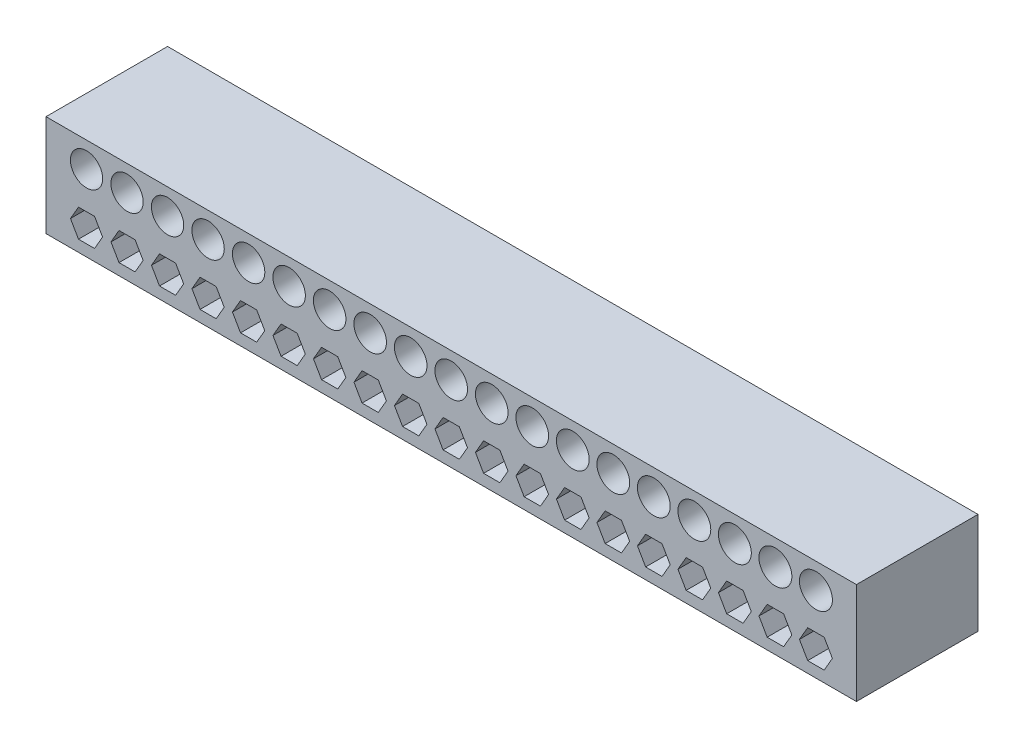
SolidWorks part; units mm, degrees
ref_plane "Front Plane" through (0, 0, 0) normal (0, 0, 1) x (1, 0, 0)
ref_plane "Top Plane" through (0, 0, 0) normal (0, 1, 0) x (1, 0, 0)
ref_plane "Right Plane" through (0, 0, 0) normal (1, 0, 0) x (0, 0, -1)
sketch "Sketch1" plane through (0, 0, 0) normal (0, 0, 1) x (1, 0, 0)
  line L0 (-93.9567, 6.25) -> (-91.9783, 9.6766) construction
  line L1 (-100, -12.5) -> (100, -12.5)
  line L2 (-100, -12.5) -> (-100, 12.5)
  line L3 (-100, 12.5) -> (100, 12.5)
  line L4 (100, -12.5) -> (100, 12.5)
  line L5 (-100, -12.5) -> (100, 12.5) construction
  line L6 (0, 12.5) -> (0, 0)
  line L7 (-91.9783, 9.6766) -> (-88.0217, 9.6766) construction
  line L8 (-88.0217, 9.6766) -> (-86.0433, 6.25) construction
  line L9 (-88.0217, 2.8234) -> (-91.9783, 2.8234) construction
  line L10 (-86.0433, 6.25) -> (-88.0217, 2.8234) construction
  line L11 (-91.9783, 2.8234) -> (-93.9567, 6.25) construction
  line L12 (-93.9567, 6.25) -> (-91.9783, 9.6766) construction
  line L13 (-91.9783, 9.6766) -> (-88.0217, 9.6766) construction
  line L14 (-88.0217, 9.6766) -> (-86.0433, 6.25) construction
  line L15 (-88.0217, 2.8234) -> (-91.9783, 2.8234) construction
  line L16 (-86.0433, 6.25) -> (-88.0217, 2.8234) construction
  line L17 (-91.9783, 2.8234) -> (-93.9567, 6.25) construction
  line L18 (0, 0) -> (0, -12.5)
  line L25 (-3.9567, -6.25) -> (-1.9783, -2.8234) construction
  line L26 (-13.9567, -6.25) -> (-11.9783, -2.8234) construction
  line L27 (-1.9783, -2.8234) -> (1.9783, -2.8234) construction
  line L28 (1.9783, -2.8234) -> (3.9567, -6.25) construction
  line L29 (1.9783, -9.6766) -> (-1.9783, -9.6766) construction
  line L30 (3.9567, -6.25) -> (1.9783, -9.6766) construction
  line L31 (-1.9783, -9.6766) -> (-3.9567, -6.25) construction
  line L32 (-1.9783, -9.6766) -> (1.9783, -2.8234) construction
  line L33 (-3.9567, -6.25) -> (3.9567, -6.25) construction
  line L34 (1.9783, -9.6766) -> (-1.9783, -2.8234) construction
  line L35 (-11.9783, -2.8234) -> (-8.0217, -2.8234) construction
  line L36 (-8.0217, -2.8234) -> (-6.0433, -6.25) construction
  line L37 (-6.0433, -6.25) -> (-8.0217, -9.6766) construction
  line L38 (-11.9783, -9.6766) -> (-13.9567, -6.25) construction
  line L39 (-8.0217, -9.6766) -> (-11.9783, -9.6766) construction
  line L40 (-23.9567, -6.25) -> (-21.9783, -2.8234) construction
  line L41 (-21.9783, -2.8234) -> (-18.0217, -2.8234) construction
  line L42 (-18.0217, -2.8234) -> (-16.0433, -6.25) construction
  line L43 (-16.0433, -6.25) -> (-18.0217, -9.6766) construction
  line L44 (-21.9783, -9.6766) -> (-23.9567, -6.25) construction
  line L45 (-18.0217, -9.6766) -> (-21.9783, -9.6766) construction
  line L46 (-33.9567, -6.25) -> (-31.9783, -2.8234) construction
  line L47 (-31.9783, -2.8234) -> (-28.0217, -2.8234) construction
  line L48 (-28.0217, -2.8234) -> (-26.0433, -6.25) construction
  line L49 (-26.0433, -6.25) -> (-28.0217, -9.6766) construction
  line L50 (-31.9783, -9.6766) -> (-33.9567, -6.25) construction
  line L51 (-28.0217, -9.6766) -> (-31.9783, -9.6766) construction
  line L52 (-43.9567, -6.25) -> (-41.9783, -2.8234) construction
  line L53 (-41.9783, -2.8234) -> (-38.0217, -2.8234) construction
  line L54 (-38.0217, -2.8234) -> (-36.0433, -6.25) construction
  line L55 (-36.0433, -6.25) -> (-38.0217, -9.6766) construction
  line L56 (-41.9783, -9.6766) -> (-43.9567, -6.25) construction
  line L57 (-38.0217, -9.6766) -> (-41.9783, -9.6766) construction
  line L58 (-53.9567, -6.25) -> (-51.9783, -2.8234) construction
  line L59 (-51.9783, -2.8234) -> (-48.0217, -2.8234) construction
  line L60 (-48.0217, -2.8234) -> (-46.0433, -6.25) construction
  line L61 (-46.0433, -6.25) -> (-48.0217, -9.6766) construction
  line L62 (-51.9783, -9.6766) -> (-53.9567, -6.25) construction
  line L63 (-48.0217, -9.6766) -> (-51.9783, -9.6766) construction
  line L64 (-63.9567, -6.25) -> (-61.9783, -2.8234) construction
  line L65 (-61.9783, -2.8234) -> (-58.0217, -2.8234) construction
  line L66 (-58.0217, -2.8234) -> (-56.0433, -6.25) construction
  line L67 (-56.0433, -6.25) -> (-58.0217, -9.6766) construction
  line L68 (-61.9783, -9.6766) -> (-63.9567, -6.25) construction
  line L69 (-58.0217, -9.6766) -> (-61.9783, -9.6766) construction
  line L70 (-73.9567, -6.25) -> (-71.9783, -2.8234) construction
  line L71 (-71.9783, -2.8234) -> (-68.0217, -2.8234) construction
  line L72 (-68.0217, -2.8234) -> (-66.0433, -6.25) construction
  line L73 (-66.0433, -6.25) -> (-68.0217, -9.6766) construction
  line L74 (-71.9783, -9.6766) -> (-73.9567, -6.25) construction
  line L75 (-68.0217, -9.6766) -> (-71.9783, -9.6766) construction
  line L76 (-83.9567, -6.25) -> (-81.9783, -2.8234) construction
  line L77 (-81.9783, -2.8234) -> (-78.0217, -2.8234) construction
  line L78 (-78.0217, -2.8234) -> (-76.0433, -6.25) construction
  line L79 (-76.0433, -6.25) -> (-78.0217, -9.6766) construction
  line L80 (-81.9783, -9.6766) -> (-83.9567, -6.25) construction
  line L81 (-78.0217, -9.6766) -> (-81.9783, -9.6766) construction
  line L82 (-93.9567, -6.25) -> (-91.9783, -2.8234) construction
  line L83 (-91.9783, -2.8234) -> (-88.0217, -2.8234) construction
  line L84 (-88.0217, -2.8234) -> (-86.0433, -6.25) construction
  line L85 (-86.0433, -6.25) -> (-88.0217, -9.6766) construction
  line L86 (-91.9783, -9.6766) -> (-93.9567, -6.25) construction
  line L87 (-88.0217, -9.6766) -> (-91.9783, -9.6766) construction
  line L88 (-3.9567, -6.25) -> (-13.9567, -6.25) construction
  line L89 (-91.9812, -2.8184) -> (-88.0188, -2.8184)
  line L90 (-88.0188, -2.8184) -> (-86.0375, -6.25)
  line L91 (-86.0375, -6.25) -> (-88.0188, -9.6816)
  line L92 (-88.0188, -9.6816) -> (-91.9812, -9.6816)
  line L93 (-91.9812, -9.6816) -> (-93.9625, -6.25)
  line L94 (-93.9625, -6.25) -> (-91.9812, -2.8184)
  line L95 (-81.9841, -2.8134) -> (-78.0159, -2.8134)
  line L96 (-78.0159, -2.8134) -> (-76.0318, -6.25)
  line L97 (-76.0318, -6.25) -> (-78.0159, -9.6866)
  line L98 (-78.0159, -9.6866) -> (-81.9841, -9.6866)
  line L99 (-81.9841, -9.6866) -> (-83.9682, -6.25)
  line L100 (-83.9682, -6.25) -> (-81.9841, -2.8134)
  line L101 (-71.987, -2.8084) -> (-68.013, -2.8084)
  line L102 (-68.013, -2.8084) -> (-66.026, -6.25)
  line L103 (-66.026, -6.25) -> (-68.013, -9.6916)
  line L104 (-68.013, -9.6916) -> (-71.987, -9.6916)
  line L105 (-71.987, -9.6916) -> (-73.974, -6.25)
  line L106 (-73.974, -6.25) -> (-71.987, -2.8084)
  line L107 (-61.9899, -2.8034) -> (-58.0101, -2.8034)
  line L108 (-58.0101, -2.8034) -> (-56.0202, -6.25)
  line L109 (-56.0202, -6.25) -> (-58.0101, -9.6966)
  line L110 (-58.0101, -9.6966) -> (-61.9899, -9.6966)
  line L111 (-61.9899, -9.6966) -> (-63.9798, -6.25)
  line L112 (-63.9798, -6.25) -> (-61.9899, -2.8034)
  line L113 (-51.9928, -2.7984) -> (-48.0072, -2.7984)
  line L114 (-48.0072, -2.7984) -> (-46.0144, -6.25)
  line L115 (-46.0144, -6.25) -> (-48.0072, -9.7016)
  line L116 (-48.0072, -9.7016) -> (-51.9928, -9.7016)
  line L117 (-51.9928, -9.7016) -> (-53.9856, -6.25)
  line L118 (-53.9856, -6.25) -> (-51.9928, -2.7984)
  line L119 (-41.9957, -2.7934) -> (-38.0043, -2.7934)
  line L120 (-38.0043, -2.7934) -> (-36.0087, -6.25)
  line L121 (-36.0087, -6.25) -> (-38.0043, -9.7066)
  line L122 (-38.0043, -9.7066) -> (-41.9957, -9.7066)
  line L123 (-41.9957, -9.7066) -> (-43.9913, -6.25)
  line L124 (-43.9913, -6.25) -> (-41.9957, -2.7934)
  line L125 (-31.9986, -2.7884) -> (-28.0014, -2.7884)
  line L126 (-28.0014, -2.7884) -> (-26.0029, -6.25)
  line L127 (-26.0029, -6.25) -> (-28.0014, -9.7116)
  line L128 (-28.0014, -9.7116) -> (-31.9986, -9.7116)
  line L129 (-31.9986, -9.7116) -> (-33.9971, -6.25)
  line L130 (-33.9971, -6.25) -> (-31.9986, -2.7884)
  line L131 (-22.0014, -2.7834) -> (-17.9986, -2.7834)
  line L132 (-17.9986, -2.7834) -> (-15.9971, -6.25)
  line L133 (-15.9971, -6.25) -> (-17.9986, -9.7166)
  line L134 (-17.9986, -9.7166) -> (-22.0014, -9.7166)
  line L135 (-22.0014, -9.7166) -> (-24.0029, -6.25)
  line L136 (-24.0029, -6.25) -> (-22.0014, -2.7834)
  line L137 (-12.0043, -2.7784) -> (-7.9957, -2.7784)
  line L138 (-7.9957, -2.7784) -> (-5.9913, -6.25)
  line L139 (-5.9913, -6.25) -> (-7.9957, -9.7216)
  line L140 (-7.9957, -9.7216) -> (-12.0043, -9.7216)
  line L141 (-12.0043, -9.7216) -> (-14.0087, -6.25)
  line L142 (-14.0087, -6.25) -> (-12.0043, -2.7784)
  line L143 (8.0217, -2.8234) -> (11.9783, -2.8234) construction
  line L144 (11.9783, -2.8234) -> (13.9567, -6.25) construction
  line L145 (13.9567, -6.25) -> (11.9783, -9.6766) construction
  line L146 (11.9783, -9.6766) -> (8.0217, -9.6766) construction
  line L147 (8.0217, -9.6766) -> (6.0433, -6.25) construction
  line L148 (6.0433, -6.25) -> (8.0217, -2.8234) construction
  line L149 (18.0217, -2.8234) -> (21.9783, -2.8234) construction
  line L150 (21.9783, -2.8234) -> (23.9567, -6.25) construction
  line L151 (23.9567, -6.25) -> (21.9783, -9.6766) construction
  line L152 (21.9783, -9.6766) -> (18.0217, -9.6766) construction
  line L153 (18.0217, -9.6766) -> (16.0433, -6.25) construction
  line L154 (16.0433, -6.25) -> (18.0217, -2.8234) construction
  line L155 (28.0217, -2.8234) -> (31.9783, -2.8234) construction
  line L156 (31.9783, -2.8234) -> (33.9567, -6.25) construction
  line L157 (33.9567, -6.25) -> (31.9783, -9.6766) construction
  line L158 (31.9783, -9.6766) -> (28.0217, -9.6766) construction
  line L159 (28.0217, -9.6766) -> (26.0433, -6.25) construction
  line L160 (26.0433, -6.25) -> (28.0217, -2.8234) construction
  line L161 (38.0217, -2.8234) -> (41.9783, -2.8234) construction
  line L162 (41.9783, -2.8234) -> (43.9567, -6.25) construction
  line L163 (43.9567, -6.25) -> (41.9783, -9.6766) construction
  line L164 (41.9783, -9.6766) -> (38.0217, -9.6766) construction
  line L165 (38.0217, -9.6766) -> (36.0433, -6.25) construction
  line L166 (36.0433, -6.25) -> (38.0217, -2.8234) construction
  line L167 (48.0217, -2.8234) -> (51.9783, -2.8234) construction
  line L168 (51.9783, -2.8234) -> (53.9567, -6.25) construction
  line L169 (53.9567, -6.25) -> (51.9783, -9.6766) construction
  line L170 (51.9783, -9.6766) -> (48.0217, -9.6766) construction
  line L171 (48.0217, -9.6766) -> (46.0433, -6.25) construction
  line L172 (46.0433, -6.25) -> (48.0217, -2.8234) construction
  line L173 (58.0217, -2.8234) -> (61.9783, -2.8234) construction
  line L174 (61.9783, -2.8234) -> (63.9567, -6.25) construction
  line L175 (63.9567, -6.25) -> (61.9783, -9.6766) construction
  line L176 (61.9783, -9.6766) -> (58.0217, -9.6766) construction
  line L177 (58.0217, -9.6766) -> (56.0433, -6.25) construction
  line L178 (56.0433, -6.25) -> (58.0217, -2.8234) construction
  line L179 (68.0217, -2.8234) -> (71.9783, -2.8234) construction
  line L180 (71.9783, -2.8234) -> (73.9567, -6.25) construction
  line L181 (73.9567, -6.25) -> (71.9783, -9.6766) construction
  line L182 (71.9783, -9.6766) -> (68.0217, -9.6766) construction
  line L183 (68.0217, -9.6766) -> (66.0433, -6.25) construction
  line L184 (66.0433, -6.25) -> (68.0217, -2.8234) construction
  line L185 (78.0217, -2.8234) -> (81.9783, -2.8234) construction
  line L186 (81.9783, -2.8234) -> (83.9567, -6.25) construction
  line L187 (83.9567, -6.25) -> (81.9783, -9.6766) construction
  line L188 (81.9783, -9.6766) -> (78.0217, -9.6766) construction
  line L189 (78.0217, -9.6766) -> (76.0433, -6.25) construction
  line L190 (76.0433, -6.25) -> (78.0217, -2.8234) construction
  line L191 (88.0217, -2.8234) -> (91.9783, -2.8234) construction
  line L192 (91.9783, -2.8234) -> (93.9567, -6.25) construction
  line L193 (93.9567, -6.25) -> (91.9783, -9.6766) construction
  line L194 (91.9783, -9.6766) -> (88.0217, -9.6766) construction
  line L195 (88.0217, -9.6766) -> (86.0433, -6.25) construction
  line L196 (86.0433, -6.25) -> (88.0217, -2.8234) construction
  line L197 (-2.0072, -2.7734) -> (2.0072, -2.7734)
  line L198 (2.0072, -2.7734) -> (4.0144, -6.25)
  line L199 (4.0144, -6.25) -> (2.0072, -9.7266)
  line L200 (2.0072, -9.7266) -> (-2.0072, -9.7266)
  line L201 (-2.0072, -9.7266) -> (-4.0144, -6.25)
  line L202 (-4.0144, -6.25) -> (-2.0072, -2.7734)
  line L203 (7.9899, -2.7684) -> (12.0101, -2.7684)
  line L204 (12.0101, -2.7684) -> (14.0202, -6.25)
  line L205 (14.0202, -6.25) -> (12.0101, -9.7316)
  line L206 (12.0101, -9.7316) -> (7.9899, -9.7316)
  line L207 (7.9899, -9.7316) -> (5.9798, -6.25)
  line L208 (5.9798, -6.25) -> (7.9899, -2.7684)
  line L209 (17.987, -2.7634) -> (22.013, -2.7634)
  line L210 (22.013, -2.7634) -> (24.026, -6.25)
  line L211 (24.026, -6.25) -> (22.013, -9.7366)
  line L212 (22.013, -9.7366) -> (17.987, -9.7366)
  line L213 (17.987, -9.7366) -> (15.974, -6.25)
  line L214 (15.974, -6.25) -> (17.987, -2.7634)
  line L215 (27.9841, -2.7584) -> (32.0159, -2.7584)
  line L216 (32.0159, -2.7584) -> (34.0318, -6.25)
  line L217 (34.0318, -6.25) -> (32.0159, -9.7416)
  line L218 (32.0159, -9.7416) -> (27.9841, -9.7416)
  line L219 (27.9841, -9.7416) -> (25.9682, -6.25)
  line L220 (25.9682, -6.25) -> (27.9841, -2.7584)
  line L221 (37.9812, -2.7534) -> (42.0188, -2.7534)
  line L222 (42.0188, -2.7534) -> (44.0375, -6.25)
  line L223 (44.0375, -6.25) -> (42.0188, -9.7466)
  line L224 (42.0188, -9.7466) -> (37.9812, -9.7466)
  line L225 (37.9812, -9.7466) -> (35.9625, -6.25)
  line L226 (35.9625, -6.25) -> (37.9812, -2.7534)
  line L227 (47.9783, -2.7484) -> (52.0217, -2.7484)
  line L228 (52.0217, -2.7484) -> (54.0433, -6.25)
  line L229 (54.0433, -6.25) -> (52.0217, -9.7516)
  line L230 (52.0217, -9.7516) -> (47.9783, -9.7516)
  line L231 (47.9783, -9.7516) -> (45.9567, -6.25)
  line L232 (45.9567, -6.25) -> (47.9783, -2.7484)
  line L233 (57.9755, -2.7434) -> (62.0245, -2.7434)
  line L234 (62.0245, -2.7434) -> (64.0491, -6.25)
  line L235 (64.0491, -6.25) -> (62.0245, -9.7566)
  line L236 (62.0245, -9.7566) -> (57.9755, -9.7566)
  line L237 (57.9755, -9.7566) -> (55.9509, -6.25)
  line L238 (55.9509, -6.25) -> (57.9755, -2.7434)
  line L239 (67.9726, -2.7384) -> (72.0274, -2.7384)
  line L240 (72.0274, -2.7384) -> (74.0548, -6.25)
  line L241 (74.0548, -6.25) -> (72.0274, -9.7616)
  line L242 (72.0274, -9.7616) -> (67.9726, -9.7616)
  line L243 (67.9726, -9.7616) -> (65.9452, -6.25)
  line L244 (65.9452, -6.25) -> (67.9726, -2.7384)
  line L245 (77.9697, -2.7334) -> (82.0303, -2.7334)
  line L246 (82.0303, -2.7334) -> (84.0606, -6.25)
  line L247 (84.0606, -6.25) -> (82.0303, -9.7666)
  line L248 (82.0303, -9.7666) -> (77.9697, -9.7666)
  line L249 (77.9697, -9.7666) -> (75.9394, -6.25)
  line L250 (75.9394, -6.25) -> (77.9697, -2.7334)
  line L251 (87.9668, -2.7284) -> (92.0332, -2.7284)
  line L252 (92.0332, -2.7284) -> (94.0664, -6.25)
  line L253 (94.0664, -6.25) -> (92.0332, -9.7716)
  line L254 (92.0332, -9.7716) -> (87.9668, -9.7716)
  line L255 (87.9668, -9.7716) -> (85.9336, -6.25)
  line L256 (85.9336, -6.25) -> (87.9668, -2.7284)
  circle A0 centre (-90, 6.25) radius 3.975 construction
  circle A1 centre (-90, 6.25) radius 3.975 construction
  circle A2 centre (0, 6.25) radius 3.975 construction
  circle A3 centre (-10, 6.25) radius 3.975 construction
  circle A4 centre (-20, 6.25) radius 3.975 construction
  circle A5 centre (-30, 6.25) radius 3.975 construction
  circle A6 centre (-40, 6.25) radius 3.975 construction
  circle A7 centre (-50, 6.25) radius 3.975 construction
  circle A8 centre (-60, 6.25) radius 3.975 construction
  circle A9 centre (-70, 6.25) radius 3.975 construction
  circle A10 centre (-80, 6.25) radius 3.975 construction
  circle A11 centre (-90, 6.25) radius 3.975 construction
  circle A12 centre (-90, 6.25) radius 3.98
  circle A13 centre (-80, 6.25) radius 3.985
  circle A14 centre (-70, 6.25) radius 3.99
  circle A15 centre (-60, 6.25) radius 3.995
  circle A16 centre (-50, 6.25) radius 4
  circle A17 centre (-40, 6.25) radius 4.005
  circle A18 centre (-30, 6.25) radius 4.01
  circle A19 centre (-20, 6.25) radius 4.015
  circle A20 centre (-10, 6.25) radius 4.02
  circle A21 centre (10, 6.25) radius 3.975 construction
  circle A22 centre (20, 6.25) radius 3.975 construction
  circle A23 centre (30, 6.25) radius 3.975 construction
  circle A24 centre (40, 6.25) radius 3.975 construction
  circle A25 centre (50, 6.25) radius 3.975 construction
  circle A26 centre (60, 6.25) radius 3.975 construction
  circle A27 centre (70, 6.25) radius 3.975 construction
  circle A28 centre (80, 6.25) radius 3.975 construction
  circle A29 centre (90, 6.25) radius 3.975 construction
  circle A30 centre (0, 6.25) radius 4.025
  circle A31 centre (10, 6.25) radius 4.03
  circle A32 centre (20, 6.25) radius 4.035
  circle A33 centre (30, 6.25) radius 4.04
  circle A34 centre (40, 6.25) radius 4.045
  circle A35 centre (50, 6.25) radius 4.05
  circle A36 centre (60, 6.25) radius 4.055
  circle A37 centre (70, 6.25) radius 4.06
  circle A38 centre (80, 6.25) radius 4.065
  circle A39 centre (90, 6.25) radius 4.07
  point P0 (0, 0)
  point P17 (0, 0)
  point P26 (0, -6.25)
  point P27 (0, -6.25)
  point P28 (0, -6.25)
  dimension "D2" = 200
  dimension "D1" = 25
  dimension "D4" = 10
  dimension "D5" = 0.005
  dimension "D6" = 0.01
  dimension "D7" = 0.015
  dimension "D8" = 0.02
  dimension "D9" = 0.025
  dimension "D10" = 0.03
  dimension "D11" = 0.035
  dimension "D12" = 0.04
  dimension "D13" = 0.045
  dimension "D15" = 0.05
  dimension "D16" = 0.055
  dimension "D17" = 0.06
  dimension "D18" = 0.065
  dimension "D19" = 0.07
  dimension "D20" = 0.075
  dimension "D21" = 0.08
  dimension "D22" = 0.085
  dimension "D23" = 0.09
  dimension "D24" = 0.095
  dimension "D3" = 10
  dimension "D14" = 10
extrude "Boss-Extrude1" add sketch "Sketch1" against normal blind 30 contours L18 L6 L3 L2 L1 A14 A13 A12 L93 L94 L89 L90 L91 L92 L99 L100 L95 L96 L97 L98 L105 L106 L101 L102 L103 L104 | L6 L18 L1 L4 L3
equation "\"tolerance_test_step\"= 0.01mm / 2"
equation "\"D5@Sketch1\"=\"tolerance_test_step\""
equation "\"D6@Sketch1\"=\"tolerance_test_step\"*2"
equation "\"D7@Sketch1\"=\"tolerance_test_step\"*3"
equation "\"D8@Sketch1\"=\"tolerance_test_step\"*4"
equation "\"D9@Sketch1\"=\"tolerance_test_step\"*5"
equation "\"D10@Sketch1\"=\"tolerance_test_step\"*6"
equation "\"D11@Sketch1\"=\"tolerance_test_step\"*7"
equation "\"D12@Sketch1\"=\"tolerance_test_step\"*8"
equation "\"D13@Sketch1\"=\"tolerance_test_step\"*9"
equation "\"D15@Sketch1\"=\"tolerance_test_step\"*10"
equation "\"D16@Sketch1\"=\"tolerance_test_step\"*11"
equation "\"D17@Sketch1\"=\"tolerance_test_step\"*12"
equation "\"D18@Sketch1\"=\"tolerance_test_step\"*13"
equation "\"D19@Sketch1\"=\"tolerance_test_step\"*14"
equation "\"D20@Sketch1\"=\"tolerance_test_step\"*15"
equation "\"D21@Sketch1\"=\"tolerance_test_step\"*16"
equation "\"D22@Sketch1\"=\"tolerance_test_step\"*17"
equation "\"D23@Sketch1\"=\"tolerance_test_step\"*18"
equation "\"D24@Sketch1\"=\"tolerance_test_step\"*19"
